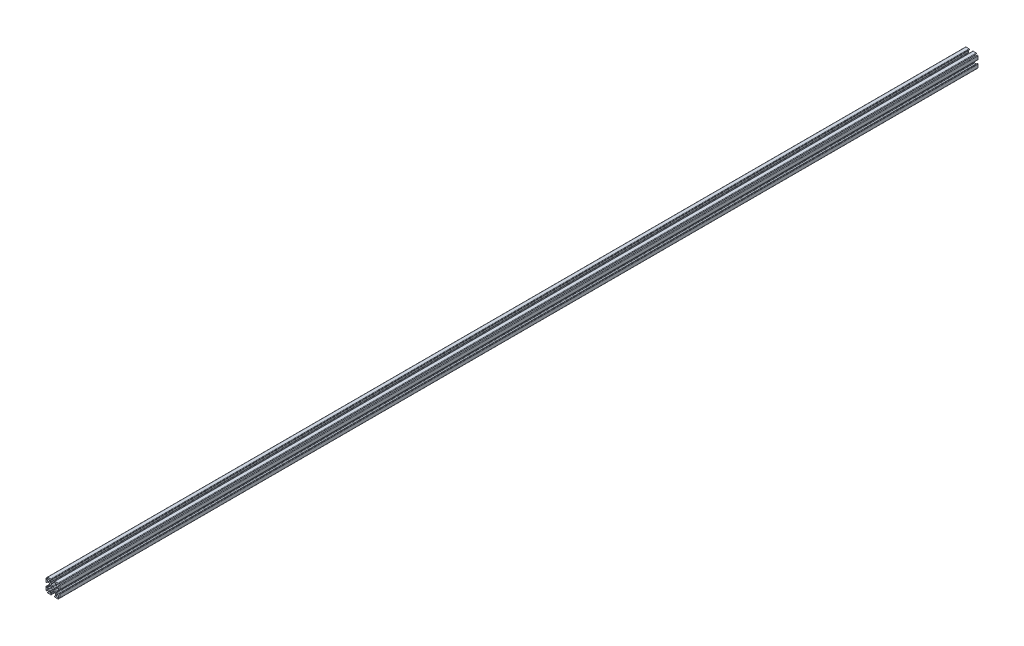
SolidWorks part; units mm, degrees
ref_plane "Front Plane" through (0, 0, 0) normal (0, 0, 1) x (1, 0, 0)
ref_plane "Top Plane" through (0, 0, 0) normal (0, 1, 0) x (1, 0, 0)
ref_plane "Right Plane" through (0, 0, 0) normal (1, 0, 0) x (0, 0, -1)
ref_plane "Plane1" through (0, 0, 0) normal (0, 0, -1) x (-1, 0, 0)
sketch "Sketch1" plane through (0, 0, 0) normal (0, 0, -1) x (-1, 0, 0)
  line L0 (6.6464, 5.9393) -> (6.1636, 5.4565)
  line L1 (5.4565, 6.1636) -> (5.9393, 6.6464)
  line L2 (5.5858, 7.5) -> (2.25, 7.5)
  line L3 (1.75, 7) -> (1.75, 6.8)
  line L4 (2.25, 6.3) -> (2.65, 6.3)
  line L5 (2.85, 6.1) -> (2.85, 4)
  line L6 (2.35, 3.5) -> (2.1, 3.5)
  line L7 (0.6, 2) -> (-0.6, 2)
  line L8 (-2.1, 3.5) -> (-2.35, 3.5)
  line L9 (-2.85, 4) -> (-2.85, 6.1)
  line L10 (-2.65, 6.3) -> (-2.25, 6.3)
  line L11 (-1.75, 6.8) -> (-1.75, 7)
  line L12 (-2.25, 7.5) -> (-5.5858, 7.5)
  line L13 (-5.9393, 6.6464) -> (-5.4565, 6.1636)
  line L14 (-6.1636, 5.4565) -> (-6.6464, 5.9393)
  line L15 (-7.5, 5.5858) -> (-7.5, 2.25)
  line L16 (-7, 1.75) -> (-6.8, 1.75)
  line L17 (-6.3, 2.25) -> (-6.3, 2.65)
  line L18 (-6.1, 2.85) -> (-4, 2.85)
  line L19 (-3.5, 2.35) -> (-3.5, 2.1)
  line L20 (-2, 0.6) -> (-2, -0.6)
  line L21 (-3.5, -2.1) -> (-3.5, -2.35)
  line L22 (-4, -2.85) -> (-6.1, -2.85)
  line L23 (-6.3, -2.65) -> (-6.3, -2.25)
  line L24 (-6.8, -1.75) -> (-7, -1.75)
  line L25 (-7.5, -2.25) -> (-7.5, -5.5858)
  line L26 (-6.6464, -5.9393) -> (-6.1636, -5.4565)
  line L27 (-5.4565, -6.1636) -> (-5.9393, -6.6464)
  line L28 (-5.5858, -7.5) -> (-2.25, -7.5)
  line L29 (-1.75, -7) -> (-1.75, -6.8)
  line L30 (-2.25, -6.3) -> (-2.65, -6.3)
  line L31 (-2.85, -6.1) -> (-2.85, -4)
  line L32 (-2.35, -3.5) -> (-2.1, -3.5)
  line L33 (-0.6, -2) -> (0.6, -2)
  line L34 (2.1, -3.5) -> (2.35, -3.5)
  line L35 (2.85, -4) -> (2.85, -6.1)
  line L36 (2.65, -6.3) -> (2.25, -6.3)
  line L37 (1.75, -6.8) -> (1.75, -7)
  line L38 (2.25, -7.5) -> (5.5858, -7.5)
  line L39 (5.9393, -6.6464) -> (5.4565, -6.1636)
  line L40 (6.1636, -5.4565) -> (6.6464, -5.9393)
  line L41 (7.5, -5.5858) -> (7.5, -2.25)
  line L42 (7, -1.75) -> (6.8, -1.75)
  line L43 (6.3, -2.25) -> (6.3, -2.65)
  line L44 (6.1, -2.85) -> (4, -2.85)
  line L45 (3.5, -2.35) -> (3.5, -2.1)
  line L46 (2, -0.6) -> (2, 0.6)
  line L47 (3.5, 2.1) -> (3.5, 2.35)
  line L48 (4, 2.85) -> (6.1, 2.85)
  line L49 (6.3, 2.65) -> (6.3, 2.25)
  line L50 (6.8, 1.75) -> (7, 1.75)
  line L51 (7.5, 2.25) -> (7.5, 5.5858)
  circle A0 centre (0, 0) radius 1.25
  arc A1 (6.1636, 5.4565) -> (5.4565, 6.1636) centre (5, 5) cw
  arc A2 (5.9393, 6.6464) -> (5.5858, 7.5) centre (5.5858, 7) ccw
  arc A3 (2.25, 7.5) -> (1.75, 7) centre (2.25, 7) ccw
  arc A4 (1.75, 6.8) -> (2.25, 6.3) centre (2.25, 6.8) ccw
  arc A5 (2.65, 6.3) -> (2.85, 6.1) centre (2.65, 6.1) cw
  arc A6 (2.85, 4) -> (2.35, 3.5) centre (2.35, 4) cw
  arc A7 (2.1, 3.5) -> (1.6, 3) centre (2.1, 3) ccw
  arc A8 (1.6, 3) -> (0.6, 2) centre (0.6, 3) cw
  arc A9 (-0.6, 2) -> (-1.6, 3) centre (-0.6, 3) cw
  arc A10 (-1.6, 3) -> (-2.1, 3.5) centre (-2.1, 3) ccw
  arc A11 (-2.35, 3.5) -> (-2.85, 4) centre (-2.35, 4) cw
  arc A12 (-2.85, 6.1) -> (-2.65, 6.3) centre (-2.65, 6.1) cw
  arc A13 (-2.25, 6.3) -> (-1.75, 6.8) centre (-2.25, 6.8) ccw
  arc A14 (-1.75, 7) -> (-2.25, 7.5) centre (-2.25, 7) ccw
  arc A15 (-5.5858, 7.5) -> (-5.9393, 6.6464) centre (-5.5858, 7) ccw
  arc A16 (-5.4565, 6.1636) -> (-6.1636, 5.4565) centre (-5, 5) cw
  arc A17 (-6.6464, 5.9393) -> (-7.5, 5.5858) centre (-7, 5.5858) ccw
  arc A18 (-7.5, 2.25) -> (-7, 1.75) centre (-7, 2.25) ccw
  arc A19 (-6.8, 1.75) -> (-6.3, 2.25) centre (-6.8, 2.25) ccw
  arc A20 (-6.3, 2.65) -> (-6.1, 2.85) centre (-6.1, 2.65) cw
  arc A21 (-4, 2.85) -> (-3.5, 2.35) centre (-4, 2.35) cw
  arc A22 (-3.5, 2.1) -> (-3, 1.6) centre (-3, 2.1) ccw
  arc A23 (-3, 1.6) -> (-2, 0.6) centre (-3, 0.6) cw
  arc A24 (-2, -0.6) -> (-3, -1.6) centre (-3, -0.6) cw
  arc A25 (-3, -1.6) -> (-3.5, -2.1) centre (-3, -2.1) ccw
  arc A26 (-3.5, -2.35) -> (-4, -2.85) centre (-4, -2.35) cw
  arc A27 (-6.1, -2.85) -> (-6.3, -2.65) centre (-6.1, -2.65) cw
  arc A28 (-6.3, -2.25) -> (-6.8, -1.75) centre (-6.8, -2.25) ccw
  arc A29 (-7, -1.75) -> (-7.5, -2.25) centre (-7, -2.25) ccw
  arc A30 (-7.5, -5.5858) -> (-6.6464, -5.9393) centre (-7, -5.5858) ccw
  arc A31 (-6.1636, -5.4565) -> (-5.4565, -6.1636) centre (-5, -5) cw
  arc A32 (-5.9393, -6.6464) -> (-5.5858, -7.5) centre (-5.5858, -7) ccw
  arc A33 (-2.25, -7.5) -> (-1.75, -7) centre (-2.25, -7) ccw
  arc A34 (-1.75, -6.8) -> (-2.25, -6.3) centre (-2.25, -6.8) ccw
  arc A35 (-2.65, -6.3) -> (-2.85, -6.1) centre (-2.65, -6.1) cw
  arc A36 (-2.85, -4) -> (-2.35, -3.5) centre (-2.35, -4) cw
  arc A37 (-2.1, -3.5) -> (-1.6, -3) centre (-2.1, -3) ccw
  arc A38 (-1.6, -3) -> (-0.6, -2) centre (-0.6, -3) cw
  arc A39 (0.6, -2) -> (1.6, -3) centre (0.6, -3) cw
  arc A40 (1.6, -3) -> (2.1, -3.5) centre (2.1, -3) ccw
  arc A41 (2.35, -3.5) -> (2.85, -4) centre (2.35, -4) cw
  arc A42 (2.85, -6.1) -> (2.65, -6.3) centre (2.65, -6.1) cw
  arc A43 (2.25, -6.3) -> (1.75, -6.8) centre (2.25, -6.8) ccw
  arc A44 (1.75, -7) -> (2.25, -7.5) centre (2.25, -7) ccw
  arc A45 (5.5858, -7.5) -> (5.9393, -6.6464) centre (5.5858, -7) ccw
  arc A46 (5.4565, -6.1636) -> (6.1636, -5.4565) centre (5, -5) cw
  arc A47 (6.6464, -5.9393) -> (7.5, -5.5858) centre (7, -5.5858) ccw
  arc A48 (7.5, -2.25) -> (7, -1.75) centre (7, -2.25) ccw
  arc A49 (6.8, -1.75) -> (6.3, -2.25) centre (6.8, -2.25) ccw
  arc A50 (6.3, -2.65) -> (6.1, -2.85) centre (6.1, -2.65) cw
  arc A51 (4, -2.85) -> (3.5, -2.35) centre (4, -2.35) cw
  arc A52 (3.5, -2.1) -> (3, -1.6) centre (3, -2.1) ccw
  arc A53 (3, -1.6) -> (2, -0.6) centre (3, -0.6) cw
  arc A54 (2, 0.6) -> (3, 1.6) centre (3, 0.6) cw
  arc A55 (3, 1.6) -> (3.5, 2.1) centre (3, 2.1) ccw
  arc A56 (3.5, 2.35) -> (4, 2.85) centre (4, 2.35) cw
  arc A57 (6.1, 2.85) -> (6.3, 2.65) centre (6.1, 2.65) cw
  arc A58 (6.3, 2.25) -> (6.8, 1.75) centre (6.8, 2.25) ccw
  arc A59 (7, 1.75) -> (7.5, 2.25) centre (7, 2.25) ccw
  arc A60 (7.5, 5.5858) -> (6.6464, 5.9393) centre (7, 5.5858) ccw
extrude "Boss-Extrude1" add sketch "Sketch1" against normal blind 1000
